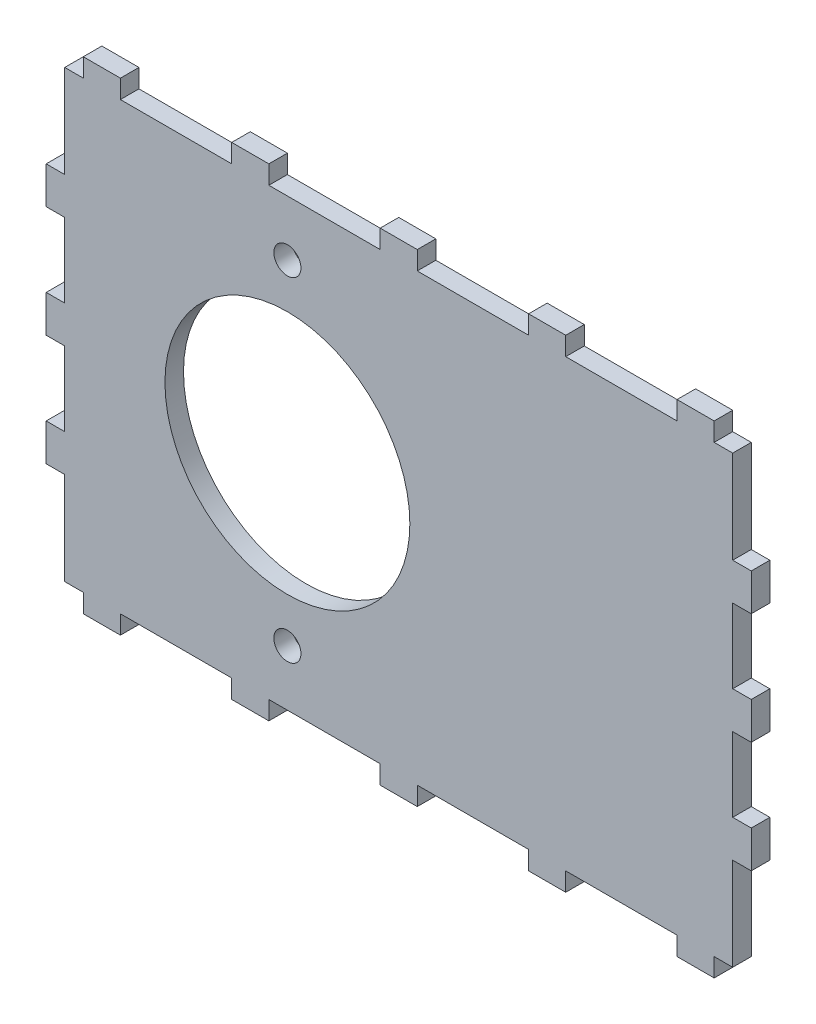
SolidWorks part; units mm, degrees
ref_plane "Ön Düzlem" through (0, 0, 0) normal (0, 0, 1) x (1, 0, 0)
ref_plane "Üst Düzlem" through (0, 0, 0) normal (0, 1, 0) x (1, 0, 0)
ref_plane "Sağ Düzlem" through (0, 0, 0) normal (1, 0, 0) x (0, 0, -1)
sketch "Sketch1" plane through (0, 0, 0) normal (0, 0, 1) x (1, 0, 0)
  line L0 (-85, 60) -> (-85, 65)
  line L1 (-90, -60) -> (-85, -60)
  line L2 (-90, -60) -> (-90, -35)
  line L3 (-90, 60) -> (-85, 60)
  line L4 (90, -60) -> (90, -35)
  line L5 (-90, -60) -> (90, 60) construction
  line L6 (-90, 60) -> (90, -60) construction
  line L7 (-85, 65) -> (-75, 65)
  line L8 (-75, 65) -> (-75, 60)
  line L9 (-45, 60) -> (-45, 65)
  line L10 (-35, 65) -> (-35, 60)
  line L11 (-45, 65) -> (-35, 65)
  line L12 (-5, 60) -> (-5, 65)
  line L13 (5, 65) -> (5, 60)
  line L14 (-5, 65) -> (5, 65)
  line L15 (35, 60) -> (35, 65)
  line L16 (45, 65) -> (45, 60)
  line L17 (35, 65) -> (45, 65)
  line L18 (75, 60) -> (75, 65)
  line L19 (85, 65) -> (85, 60)
  line L20 (75, 65) -> (85, 65)
  line L21 (-75, 60) -> (-45, 60)
  line L22 (-35, 60) -> (-5, 60)
  line L23 (5, 60) -> (35, 60)
  line L24 (45, 60) -> (75, 60)
  line L25 (85, 60) -> (90, 60)
  line L26 (-95, 0) -> (95, 0) construction
  line L27 (0, -60) -> (0, 60) construction
  line L28 (-90, 35) -> (-95, 35)
  line L29 (-95, 35) -> (-95, 25)
  line L30 (-95, 25) -> (-90, 25)
  line L31 (-95, -5) -> (-90, -5)
  line L32 (-90, 5) -> (-95, 5)
  line L33 (-95, 5) -> (-95, -5)
  line L34 (-95, -35) -> (-90, -35)
  line L35 (-90, -25) -> (-95, -25)
  line L36 (-95, -25) -> (-95, -35)
  line L37 (95, 25) -> (90, 25)
  line L38 (90, 35) -> (95, 35)
  line L39 (95, 35) -> (95, 25)
  line L40 (90, 5) -> (95, 5)
  line L41 (95, 5) -> (95, -5)
  line L42 (95, -5) -> (90, -5)
  line L43 (90, -25) -> (95, -25)
  line L44 (95, -25) -> (95, -35)
  line L45 (95, -35) -> (90, -35)
  line L46 (85, -65) -> (85, -60)
  line L47 (75, -65) -> (85, -65)
  line L48 (75, -60) -> (75, -65)
  line L49 (45, -65) -> (45, -60)
  line L50 (35, -65) -> (45, -65)
  line L51 (35, -60) -> (35, -65)
  line L52 (5, -65) -> (5, -60)
  line L53 (-5, -65) -> (5, -65)
  line L55 (-35, -65) -> (-35, -60)
  line L56 (-45, -65) -> (-35, -65)
  line L57 (-45, -60) -> (-45, -65)
  line L58 (-75, -65) -> (-75, -60)
  line L59 (-85, -65) -> (-75, -65)
  line L60 (-85, -60) -> (-85, -65)
  line L61 (-75, -60) -> (-45, -60)
  line L63 (5, -60) -> (35, -60)
  line L64 (45, -60) -> (75, -60)
  line L65 (85, -60) -> (90, -60)
  line L66 (-90, -25) -> (-90, -5)
  line L67 (-90, 5) -> (-90, 25)
  line L68 (-90, 35) -> (-90, 60)
  line L69 (90, 35) -> (90, 60)
  line L70 (90, 5) -> (90, 25)
  line L71 (90, -25) -> (90, -5)
  line L72 (-35, -60) -> (-5, -60)
  line L73 (-5, -60) -> (-5, -65)
  circle A0 centre (-30, 0) radius 33
  circle A1 centre (-30, 0) radius 45 construction
  circle A2 centre (-30, -45) radius 3.65
  circle A3 centre (-30, 45) radius 3.65
  point P0 (0, 0)
  dimension "D3" = 66
  dimension "D5" = 90
  dimension "D6" = 7.3
  dimension "D1" = 120
  dimension "D2" = 180
  dimension "D4" = 30
  dimension "D7" = 10
  dimension "D8" = 5
  dimension "D9" = 5
  dimension "D11" = 30
  dimension "D12" = 5
  dimension "D13" = 10
  dimension "D14" = 25
  dimension "D16" = 30
  dimension "D17" = 20
  dimension "D18" = 30
  dimension "D10" = 5
  dimension "D15" = 3
extrude "Boss-Extrude1" add sketch "Sketch1" along normal blind 5
